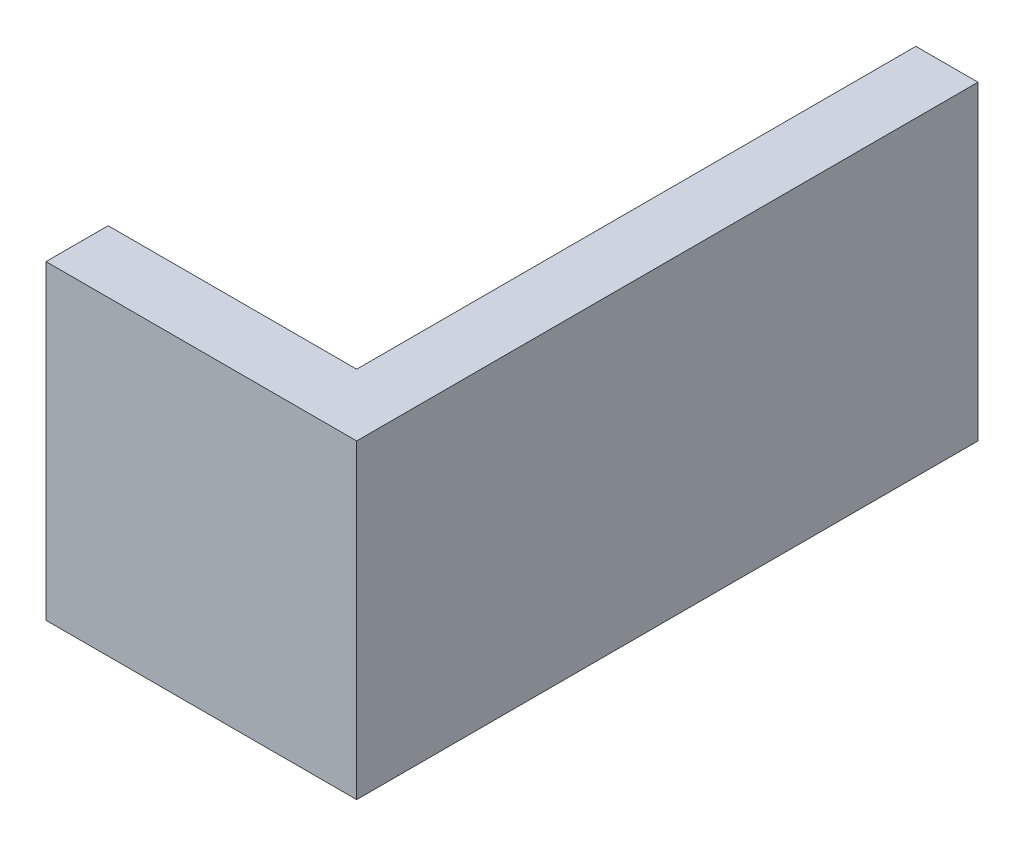
SolidWorks part; units mm, degrees
ref_plane "Front Plane" through (0, 0, 0) normal (0, 0, 1) x (1, 0, 0)
ref_plane "Top Plane" through (0, 0, 0) normal (0, 1, 0) x (1, 0, 0)
ref_plane "Right Plane" through (0, 0, 0) normal (1, 0, 0) x (0, 0, -1)
sketch "Sketch2" plane through (0, 0, 0) normal (0, 1, 0) x (1, 0, 0)
  line L0 (0, 0) -> (0, 22.86)
  line L1 (0, 22.86) -> (2.54, 22.86)
  line L2 (2.54, 22.86) -> (2.54, -2.54)
  line L3 (2.54, -2.54) -> (-10.16, -2.54)
  line L4 (-10.16, -2.54) -> (-10.16, 0)
  line L5 (-10.16, 0) -> (0, 0)
  dimension "D1" = 25.4
  dimension "D2" = 2.54
  dimension "D3" = 2.54
  dimension "D4" = 12.7
extrude "Boss-Extrude1" add sketch "Sketch2" along normal blind 12.7
sketch "Sketch3" plane through (0, 0, 0) normal (0, 0, -1) x (-1, 0, 0)
  line L0 (10.16, 6.35) -> (27.2706, 6.35) construction
  line L1 (10.16, 12.7) -> (10.16, 0) construction
